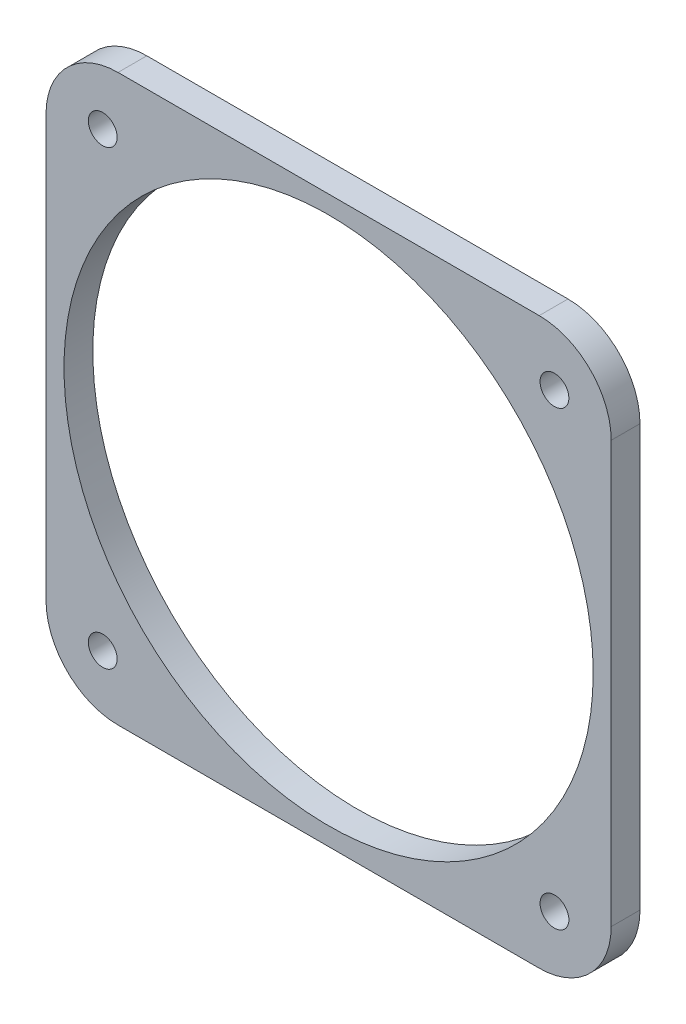
SolidWorks part; units mm, degrees
material "ABS"
ref_plane "Front Plane" through (0, 0, 0) normal (0, 0, 1) x (1, 0, 0)
ref_plane "Top Plane" through (0, 0, 0) normal (0, 1, 0) x (1, 0, 0)
ref_plane "Right Plane" through (0, 0, 0) normal (1, 0, 0) x (0, 0, -1)
sketch "Sketch1" plane through (0, 0, 0) normal (0, 0, 1) x (1, 0, 0)
  line L1 (-39.25, -39.25) -> (39.25, -39.25)
  line L2 (-39.25, -39.25) -> (-39.25, 39.25)
  line L3 (-39.25, 39.25) -> (39.25, 39.25)
  line L4 (39.25, -39.25) -> (39.25, 39.25)
  line L5 (-39.25, -39.25) -> (39.25, 39.25) construction
  line L6 (-39.25, 39.25) -> (39.25, -39.25) construction
  point P0 (0, 0)
  dimension "D1" = 78.5
extrude "Boss-Extrude1" add sketch "Sketch1" along normal mid plane 4
fillet "Fillet1" radius 10 4 edges at (-39.25, -39.25, 0) (39.25, -39.25, 0) (39.25, 39.25, 0) (-39.25, 39.25, 0)
sketch "Sketch2" plane through (0, 0, 2) normal (0, 0, 1) x (1, 0, 0)
  line L0 (0, 0) -> (-35355.3391, 35355.3391) construction
  line L1 (0, 0) -> (0, 50000) construction
  line L2 (0, 0) -> (-50000, 0) construction
  circle A0 centre (-31.3713, 31.3713) radius 2
  arc A8 (-29.25, 39.25) -> (-39.25, 29.25) centre (-29.25, 29.25) ccw construction
  circle A9 centre (-31.3713, -31.3713) radius 2
  circle A10 centre (31.3713, 31.3713) radius 2
  circle A11 centre (31.3713, -31.3713) radius 2
  dimension "D2" = 4
  dimension "D3" = 3
  dimension "D1" = 45
extrude "Cut-Extrude1" cut sketch "Sketch2" against normal through all
sketch "Sketch3" plane through (0, 0, 2) normal (0, 0, 1) x (1, 0, 0)
  circle A0 centre (0, 0) radius 36.75
  dimension "D1" = 73.5
extrude "Cut-Extrude2" cut sketch "Sketch3" against normal through all
